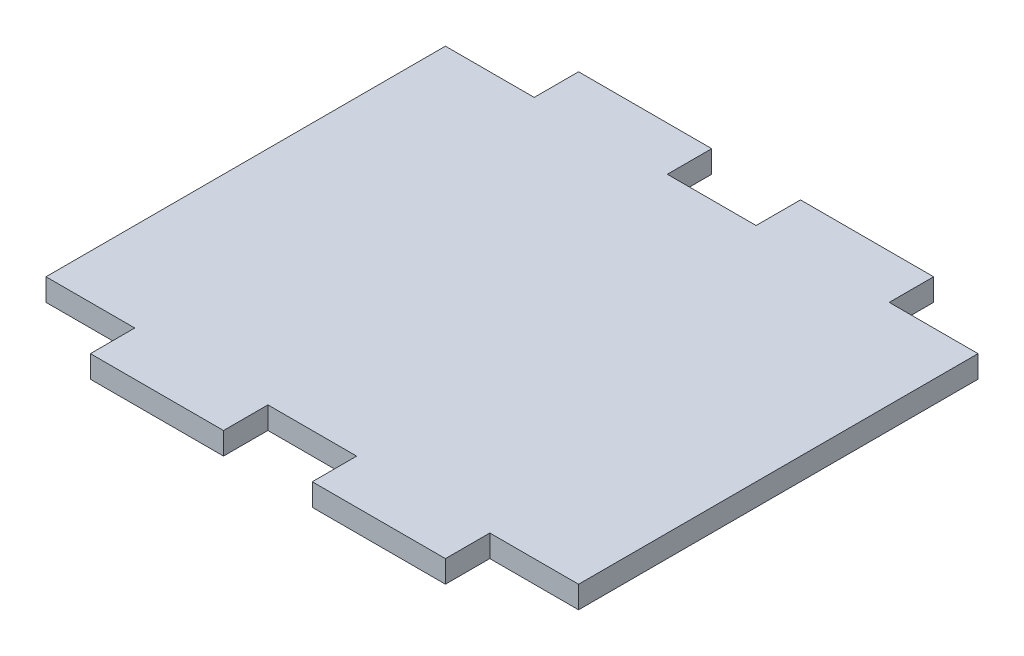
SolidWorks part; units mm, degrees
ref_plane "Front Plane" through (0, 0, 0) normal (0, 0, 1) x (1, 0, 0)
ref_plane "Top Plane" through (0, 0, 0) normal (0, 1, 0) x (1, 0, 0)
ref_plane "Right Plane" through (0, 0, 0) normal (1, 0, 0) x (0, 0, -1)
sketch "Sketch1" plane through (0, 0, 0) normal (0, 0, 1) x (1, 0, 0)
  line L0 (-432.6003, 194.7721) -> (-356.4003, 194.7721)
  line L1 (-356.4003, 194.7721) -> (-356.4003, 197.9471)
  line L2 (-356.4003, 197.9471) -> (-432.6003, 197.9471)
  line L3 (-432.6003, 197.9471) -> (-432.6003, 194.7721)
  dimension "D1" = 3.175
  dimension "D2" = 76.2
extrude "Boss-Extrude1" add sketch "Sketch1" against normal blind 69.85 contours L2 L3 L0 L1
sketch "Sketch2" plane through (0, 197.9471, 0) normal (0, 1, 0) x (1, 0, 0)
  line L0 (-248.8154, 6.35) -> (-513.3483, 6.35) construction
  line L1 (-356.4003, 0) -> (-369.1003, 0)
  line L2 (-356.4003, 0) -> (-356.4003, 6.35)
  line L3 (-356.4003, 6.35) -> (-369.1003, 6.35)
  line L4 (-369.1003, 0) -> (-369.1003, 6.35)
  line L5 (-356.4003, 0) -> (-432.6003, 0) construction
  line L6 (-388.1503, 0) -> (-400.8503, 0)
  line L7 (-388.1503, 0) -> (-388.1503, 6.35)
  line L8 (-388.1503, 6.35) -> (-400.8503, 6.35)
  line L9 (-400.8503, 0) -> (-400.8503, 6.35)
  line L10 (-513.3483, 63.5) -> (-248.8154, 63.5) construction
  line L11 (-432.6003, 0) -> (-419.9003, 0)
  line L12 (-432.6003, 0) -> (-432.6003, 6.35)
  line L13 (-432.6003, 6.35) -> (-419.9003, 6.35)
  line L14 (-419.9003, 0) -> (-419.9003, 6.35)
  line L15 (-356.4003, 69.85) -> (-369.1003, 69.85)
  line L16 (-356.4003, 69.85) -> (-356.4003, 63.5)
  line L17 (-356.4003, 63.5) -> (-369.1003, 63.5)
  line L18 (-369.1003, 69.85) -> (-369.1003, 63.5)
  line L19 (-356.4003, 69.85) -> (-432.6003, 69.85) construction
  line L20 (-388.1503, 63.5) -> (-400.8503, 63.5)
  line L21 (-388.1503, 63.5) -> (-388.1503, 69.85)
  line L22 (-388.1503, 69.85) -> (-400.8503, 69.85)
  line L23 (-400.8503, 63.5) -> (-400.8503, 69.85)
  line L25 (-432.6003, 69.85) -> (-419.9003, 69.85)
  line L26 (-432.6003, 69.85) -> (-432.6003, 63.5)
  line L27 (-432.6003, 63.5) -> (-419.9003, 63.5)
  line L28 (-419.9003, 69.85) -> (-419.9003, 63.5)
  dimension "D1" = 12.7
  dimension "D2" = 12.7
  dimension "D3" = 12.7
  dimension "D4" = 19.05
  dimension "D5" = 12.7
  dimension "D6" = 12.7
  dimension "D7" = 12.7
  dimension "D8" = 19.05
extrude "Cut-Extrude1" cut sketch "Sketch2" against normal through all
